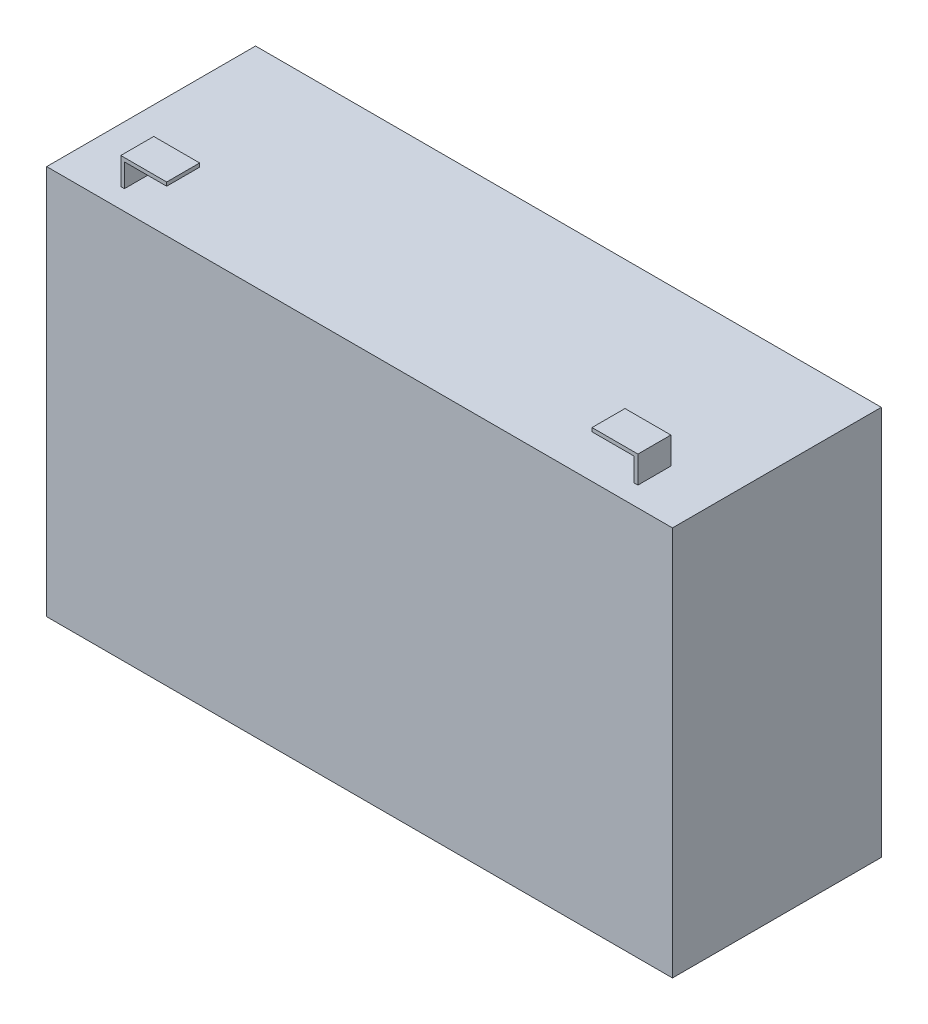
SolidWorks part; units mm, degrees
material "ABS"
ref_plane "Front Plane" through (0, 0, 0) normal (0, 0, 1) x (1, 0, 0)
ref_plane "Top Plane" through (0, 0, 0) normal (0, 1, 0) x (1, 0, 0)
ref_plane "Right Plane" through (0, 0, 0) normal (1, 0, 0) x (0, 0, -1)
sketch "Sketch2" plane through (0, 0, 0) normal (0, 0, 1) x (1, 0, 0)
  line L1 (0, 0) -> (150.6728, 0)
  line L2 (0, 0) -> (0, 93.853)
  line L3 (0, 93.853) -> (150.6728, 93.853)
  line L4 (150.6728, 0) -> (150.6728, 93.853)
  dimension "D1" = 150.6728
  dimension "D2" = 93.853
extrude "Extrude1" add sketch "Sketch2" along normal blind 50.292
sketch "Sketch3" plane through (0, 93.853, 0) normal (0, 1, 0) x (-1, 0, 0)
  line L1 (-13.081, 37.592) -> (-13.97, 37.592)
  line L2 (-13.081, 37.592) -> (-13.081, 45.5295)
  line L3 (-13.081, 45.5295) -> (-13.97, 45.5295)
  line L4 (-13.97, 37.592) -> (-13.97, 45.5295)
  line L5 (-137.5918, 45.5295) -> (-136.7028, 45.5295)
  line L6 (-137.5918, 45.5295) -> (-137.5918, 37.592)
  line L7 (-137.5918, 37.592) -> (-136.7028, 37.592)
  line L8 (-136.7028, 45.5295) -> (-136.7028, 37.592)
  dimension "D1" = 13.081
  dimension "D2" = 7.9375
  dimension "D3" = 0.889
  dimension "D4" = 4.7625
  dimension "D5" = 13.081
  dimension "D6" = 0.889
  dimension "D7" = 4.7625
  dimension "D8" = 7.9375
extrude "Extrude2" add sketch "Sketch3" along normal blind 6.477
sketch "Sketch5" plane through (0, 100.33, 0) normal (0, 1, 0) x (-1, 0, 0)
  line L1 (-13.081, 45.5295) -> (-24.13, 45.5295)
  line L2 (-13.081, 45.5295) -> (-13.081, 37.592)
  line L3 (-13.081, 37.592) -> (-24.13, 37.592)
  line L4 (-24.13, 45.5295) -> (-24.13, 37.592)
  line L5 (-137.5918, 45.5295) -> (-126.5428, 45.5295)
  line L6 (-137.5918, 45.5295) -> (-137.5918, 37.592)
  line L7 (-137.5918, 37.592) -> (-126.5428, 37.592)
  line L8 (-126.5428, 45.5295) -> (-126.5428, 37.592)
  dimension "D1" = 7.9375
  dimension "D2" = 11.049
  dimension "D3" = 11.049
  dimension "D4" = 7.9375
extrude "Extrude3" add sketch "Sketch5" against normal blind 0.889
